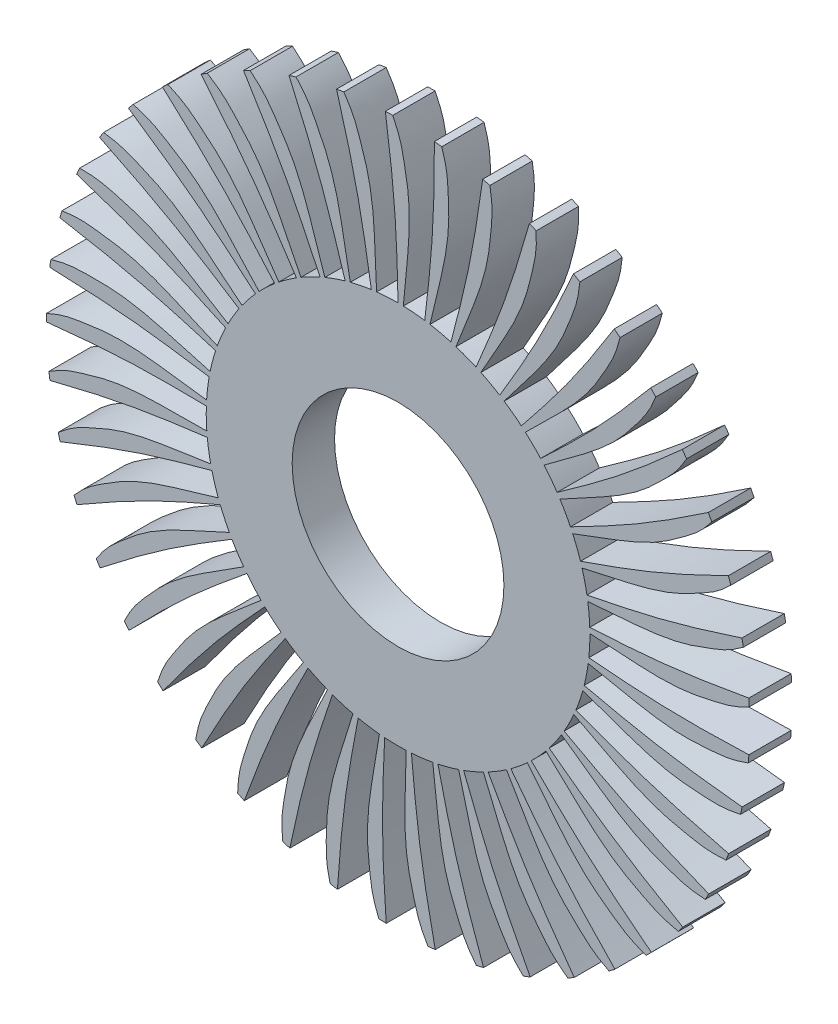
SolidWorks part; units mm, degrees
ref_plane "Front Plane" through (0, 0, 0) normal (0, 0, 1) x (1, 0, 0)
ref_plane "Top Plane" through (0, 0, 0) normal (0, 1, 0) x (1, 0, 0)
ref_plane "Right Plane" through (0, 0, 0) normal (1, 0, 0) x (0, 0, -1)
sketch "Sketch1" plane through (0, 0, 0) normal (0, 0, 1) x (1, 0, 0)
  arc A0 (49.9392, 174.1585) -> (30.1567, 178.6496) centre (0, 0) ccw
  arc A1 (-5, 332.0837) -> (-12, 331.9045) centre (0, 0) ccw
  arc A2 (41.2658, 329.5478) -> (34.309, 330.3445) centre (0, 0) ccw
  arc A3 (86.7284, 320.5976) -> (79.9501, 322.3548) centre (0, 0) ccw
  arc A4 (130.5029, 305.4073) -> (124.0352, 308.0907) centre (0, 0) ccw
  arc A5 (171.7373, 284.2726) -> (165.706, 287.83) centre (0, 0) ccw
  arc A6 (209.6291, 257.6048) -> (204.1516, 261.9671) centre (0, 0) ccw
  arc A7 (243.4407, 225.9231) -> (238.6236, 231.0052) centre (0, 0) ccw
  arc A8 (272.5139, 189.8441) -> (268.451, 195.5471) centre (0, 0) ccw
  arc A9 (296.283, 150.0699) -> (293.0534, 156.2829) centre (0, 0) ccw
  arc A10 (314.2853, 107.3748) -> (311.9518, 113.9768) centre (0, 0) ccw
  arc A11 (326.1704, 62.5898) -> (324.7784, 69.4523) centre (0, 0) ccw
  arc A12 (331.707, 16.5865) -> (331.2835, 23.576) centre (0, 0) ccw
  arc A13 (330.7872, -29.7396) -> (331.3407, -22.7592) centre (0, 0) ccw
  arc A14 (323.4291, -75.4869) -> (324.9486, -68.6514) centre (0, 0) ccw
  arc A15 (309.7757, -119.7648) -> (312.2318, -113.2074) centre (0, 0) ccw
  arc A16 (290.093, -161.7117) -> (293.4378, -155.56) centre (0, 0) ccw
  arc A17 (264.7639, -200.5111) -> (268.9323, -194.8847) centre (0, 0) ccw
  arc A18 (234.2815, -235.4078) -> (239.1923, -230.4162) centre (0, 0) ccw
  arc A19 (199.239, -265.7225) -> (204.7968, -261.463) centre (0, 0) ccw
  arc A20 (160.3186, -290.8652) -> (166.4151, -287.4206) centre (0, 0) ccw
  arc A21 (118.2778, -310.3465) -> (124.7943, -307.784) centre (0, 0) ccw
  arc A22 (73.9348, -323.7874) -> (80.7446, -322.1567) centre (0, 0) ccw
  arc A23 (28.1528, -330.926) -> (35.1233, -330.2589) centre (0, 0) ccw
  arc A24 (-18.1772, -331.6236) -> (-11.1817, -331.9331) centre (0, 0) ccw
  arc A25 (-64.1534, -325.8665) -> (-57.2691, -327.1466) centre (0, 0) ccw
  arc A26 (-108.8809, -313.7667) -> (-102.2417, -315.9925) centre (0, 0) ccw
  arc A27 (-151.4891, -295.5599) -> (-145.2244, -298.688) centre (0, 0) ccw
  arc A28 (-191.1488, -271.6003) -> (-185.3804, -275.5698) centre (0, 0) ccw
  arc A29 (-227.0881, -242.3543) -> (-221.9282, -247.088) centre (0, 0) ccw
  arc A30 (-258.6073, -208.3912) -> (-254.1564, -213.797) centre (0, 0) ccw
  arc A31 (-285.093, -170.372) -> (-281.4378, -176.3446) centre (0, 0) ccw
  arc A32 (-306.0297, -129.0367) -> (-303.2412, -135.4598) centre (0, 0) ccw
  arc A33 (-321.0098, -85.1898) -> (-319.1425, -91.9385) centre (0, 0) ccw
  arc A34 (-329.7419, -39.6848) -> (-328.832, -46.6277) centre (0, 0) ccw
  arc A35 (-332.0559, 6.5926) -> (-332.1211, -0.4094) centre (0, 0) ccw
  arc A36 (-327.9069, 52.7417) -> (-328.9459, 45.8169) centre (0, 0) ccw
  arc A37 (-317.3755, 97.8642) -> (-319.3682, 91.1515) centre (0, 0) ccw
  arc A38 (-300.6668, 141.082) -> (-303.5743, 134.7118) centre (0, 0) ccw
  arc A39 (-278.1059, 181.5537) -> (-281.8716, 175.6502) centre (0, 0) ccw
  arc A40 (-250.132, 218.4917) -> (-254.6827, 213.1697) centre (0, 0) ccw
  arc A41 (-217.2895, 251.177) -> (-222.5367, 246.5402) centre (0, 0) ccw
  arc A42 (-180.2178, 278.9734) -> (-186.0592, 275.112) centre (0, 0) ccw
  arc A43 (-139.6384, 301.3399) -> (-145.9603, 298.329) centre (0, 0) ccw
  arc A44 (-96.341, 317.8412) -> (-103.0204, 315.7395) centre (0, 0) ccw
  arc A45 (-51.1685, 328.1561) -> (-58.0754, 327.0044) centre (0, 0) ccw
  arc A46 (25.215, 179.4138) -> (5, 181.108) centre (0, 0) ccw
  arc A47 (0, 181.177) -> (-20.254, 180.0413) centre (0, 0) ccw
  arc A48 (-25.215, 179.4138) -> (-45.1138, 175.4704) centre (0, 0) ccw
  arc A49 (-49.9392, 174.1585) -> (-69.0955, 167.4841) centre (0, 0) ccw
  arc A50 (-73.6913, 165.5134) -> (-91.7324, 156.2379) centre (0, 0) ccw
  arc A51 (-96.0092, 153.6468) -> (-112.5838, 141.9507) centre (0, 0) ccw
  arc A52 (-116.4583, 138.7896) -> (-131.2438, 124.9006) centre (0, 0) ccw
  arc A53 (73.6913, 165.5134) -> (54.7264, 172.714) centre (0, 0) ccw
  arc A54 (96.0092, 153.6468) -> (78.231, 163.4167) centre (0, 0) ccw
  arc A55 (116.4583, 138.7896) -> (100.2129, 150.9387) centre (0, 0) ccw
  arc A56 (134.6408, 121.2311) -> (120.2442, 135.5228) centre (0, 0) ccw
  arc A57 (150.2026, 101.3129) -> (137.9351, 117.4692) centre (0, 0) ccw
  arc A58 (172.3096, 55.9868) -> (164.9707, 74.8986) centre (0, 0) ccw
  arc A59 (178.4245, 31.4611) -> (173.789, 51.2102) centre (0, 0) ccw
  arc A60 (181.0667, 6.323) -> (179.2248, 26.525) centre (0, 0) ccw
  arc A61 (180.1845, -18.9382) -> (181.1722, 1.3236) centre (0, 0) ccw
  arc A62 (175.7953, -43.8307) -> (179.5932, -23.9036) centre (0, 0) ccw
  arc A63 (167.9844, -67.8701) -> (174.5187, -48.6655) centre (0, 0) ccw
  arc A64 (142.7694, -111.5437) -> (154.3441, -94.8841) centre (0, 0) ccw
  arc A65 (125.8561, -130.3278) -> (139.6368, -115.4413) centre (0, 0) ccw
  arc A66 (106.4932, -146.5753) -> (122.2115, -133.7515) centre (0, 0) ccw
  arc A67 (85.0575, -159.9698) -> (102.4075, -149.4584) centre (0, 0) ccw
  arc A68 (61.9662, -170.2507) -> (80.6103, -162.2562) centre (0, 0) ccw
  arc A69 (37.6688, -177.2179) -> (57.2441, -171.896) centre (0, 0) ccw
  arc A70 (12.6383, -180.7357) -> (32.7637, -178.1899) centre (0, 0) ccw
  arc A71 (-12.6383, -180.7357) -> (7.6456, -181.0156) centre (0, 0) ccw
  arc A72 (-37.6688, -177.2179) -> (-17.6213, -180.3181) centre (0, 0) ccw
  arc A73 (-61.9662, -170.2507) -> (-42.5452, -176.1108) centre (0, 0) ccw
  arc A74 (-106.4932, -146.5753) -> (-89.4398, -157.5615) centre (0, 0) ccw
  arc A75 (-85.0575, -159.9698) -> (-66.6411, -168.4758) centre (0, 0) ccw
  arc A76 (-125.8561, -130.3278) -> (-110.4977, -143.5805) centre (0, 0) ccw
  arc A77 (-142.7694, -111.5437) -> (-129.4049, -126.8049) centre (0, 0) ccw
  arc A78 (-156.9039, -90.5885) -> (-145.7934, -107.5612) centre (0, 0) ccw
  arc A79 (-167.9844, -67.8701) -> (-159.3441, -86.2239) centre (0, 0) ccw
  arc A80 (-175.7953, -43.8307) -> (-169.7935, -63.2083) centre (0, 0) ccw
  arc A81 (-180.1845, -18.9382) -> (-176.9379, -38.9625) centre (0, 0) ccw
  arc A82 (-181.0667, 6.323) -> (-180.6385, -13.9583) centre (0, 0) ccw
  arc A83 (-178.4245, 31.4611) -> (-180.8232, 11.3175) centre (0, 0) ccw
  arc A84 (-172.3096, 55.9868) -> (-177.4883, 36.3731) centre (0, 0) ccw
  arc A85 (-162.8408, 79.4228) -> (-170.6989, 60.7207) centre (0, 0) ccw
  arc A86 (-150.2026, 101.3129) -> (-160.5869, 83.8865) centre (0, 0) ccw
  arc A87 (-134.6408, 121.2311) -> (-147.3494, 105.4195) centre (0, 0) ccw
  arc A88 (162.8408, 79.4228) -> (152.9413, 97.1291) centre (0, 0) ccw
  arc A89 (156.9039, -90.5885) -> (166.0474, -72.4802) centre (0, 0) ccw
  spline S0 degree 3 poles (5, 181.108) (8.4553, 222.2941) (14.1234, 253.7396) (4.4151, 306.3774) (2.5992, 316.7945) (-5, 332.0837) knots 0 0 0 0 0.601818 0.701818 1 1 1 1
  spline S1 degree 3 poles (0, 181.177) (-1.2031, 233.7472) (-2.136, 263.2326) (-12, 331.9045) knots 0 0 0 0 1 1 1 1
  spline S2 degree 3 poles (30.1567, 178.6496) (39.3104, 218.954) (49.2996, 249.3046) (47.0117, 302.7813) (46.6632, 313.3498) (41.2658, 329.5478) knots 0 0 0 0 0.601818 0.701818 1 1 1 1
  spline S3 degree 3 poles (25.215, 179.4138) (31.3399, 231.6398) (34.5197, 260.9681) (34.309, 330.3445) knots 0 0 0 0 1 1 1 1
  spline S4 degree 3 poles (54.7264, 172.714) (69.4003, 211.3522) (83.5164, 240.0172) (88.6932, 293.2919) (89.8189, 303.806) (86.7284, 320.5976) knots 0 0 0 0 0.601818 0.701818 1 1 1 1
  spline S5 degree 3 poles (49.9392, 174.1585) (63.273, 225.0238) (70.5035, 253.6242) (79.9501, 322.3548) knots 0 0 0 0 1 1 1 1
  spline S6 degree 3 poles (78.231, 163.4167) (98.1394, 199.6366) (116.1075, 226.0581) (128.6483, 278.0939) (131.2264, 288.349) (130.5029, 305.4073) knots 0 0 0 0 0.601818 0.701818 1 1 1 1
  spline S7 degree 3 poles (73.6913, 165.5134) (93.9744, 214.028) (105.115, 241.3438) (124.0352, 308.0907) knots 0 0 0 0 1 1 1 1
  spline S8 degree 3 poles (100.2129, 150.9387) (124.9684, 184.0354) (146.4388, 207.6991) (166.0995, 257.4831) (170.0798, 267.2797) (171.7373, 284.2726) knots 0 0 0 0 0.601818 0.701818 1 1 1 1
  spline S9 degree 3 poles (96.0092, 153.6468) (122.8468, 198.8664) (137.6806, 224.3658) (165.706, 287.83) knots 0 0 0 0 1 1 1 1
  spline S10 degree 3 poles (120.2442, 135.5228) (149.365, 164.8522) (173.9198, 185.2975) (200.3178, 231.8607) (205.6227, 241.008) (209.6291, 257.6048) knots 0 0 0 0 0.601818 0.701818 1 1 1 1
  spline S11 degree 3 poles (116.4583, 138.7896) (149.3281, 179.834) (167.5664, 203.0209) (204.1516, 261.9671) knots 0 0 0 0 1 1 1 1
  spline S12 degree 3 poles (137.9351, 117.4692) (170.8544, 142.4602) (198.0156, 159.2892) (230.6371, 201.7254) (237.1634, 210.0454) (243.4407, 225.9231) knots 0 0 0 0 0.601818 0.701818 1 1 1 1
  spline S13 degree 3 poles (134.6408, 121.2311) (172.903, 157.3015) (194.1907, 177.7244) (238.6236, 231.0052) knots 0 0 0 0 1 1 1 1
  spline S14 degree 3 poles (152.9413, 97.1291) (189.0183, 117.2955) (218.2573, 130.1806) (256.4673, 167.6638) (264.088, 174.9944) (272.5139, 189.8441) knots 0 0 0 0 0.601818 0.701818 1 1 1 1
  spline S15 degree 3 poles (150.2026, 101.3129) (193.1124, 131.7072) (217.0353, 148.9686) (268.451, 195.5471) knots 0 0 0 0 1 1 1 1
  spline S16 degree 3 poles (164.9707, 74.8986) (203.5031, 89.8477) (234.2509, 98.5381) (277.3057, 130.3387) (285.8725, 136.5374) (296.283, 150.0699) knots 0 0 0 0 0.601818 0.701818 1 1 1 1
  spline S17 degree 3 poles (162.8408, 79.4228) (209.5631, 103.5493) (235.6555, 117.3134) (293.0534, 156.2829) knots 0 0 0 0 1 1 1 1
  spline S18 degree 3 poles (173.789, 51.2102) (214.027, 60.6512) (245.685, 64.9777) (292.7466, 90.4768) (302.0927, 95.4229) (314.2853, 107.3748) knots 0 0 0 0 0.601818 0.701818 1 1 1 1
  spline S19 degree 3 poles (172.3096, 55.9868) (221.935, 73.3761) (249.689, 83.3748) (311.9518, 113.9768) knots 0 0 0 0 1 1 1 1
  spline S20 degree 3 poles (179.2248, 26.525) (220.3852, 30.2741) (252.3372, 30.1526) (302.4895, 48.8538) (312.4331, 52.4511) (326.1704, 62.5898) knots 0 0 0 0 0.601818 0.701818 1 1 1 1
  spline S21 degree 3 poles (178.4245, 31.4611) (229.9871, 41.7746) (258.8626, 47.8134) (324.7784, 69.4523) knots 0 0 0 0 1 1 1 1
  spline S22 degree 3 poles (181.1722, 1.3236) (222.4537, -0.6922) (254.0779, -5.2594) (306.3449, 6.28) (316.6923, 8.4584) (331.707, 16.5865) knots 0 0 0 0 0.601818 0.701818 1 1 1 1
  spline S23 degree 3 poles (181.0667, 6.323) (233.5628, 9.36) (262.9977, 11.3214) (331.2835, 23.576) knots 0 0 0 0 1 1 1 1
  spline S24 degree 3 poles (179.5932, -23.9036) (220.1925, -31.645) (250.8733, -40.569) (304.2375, -36.4161) (314.7874, -35.699) (330.7872, -29.7396) knots 0 0 0 0 0.601818 0.701818 1 1 1 1
  spline S25 degree 3 poles (180.1845, -18.9382) (232.5924, -23.2367) (262.0139, -25.391) (331.3407, -22.7592) knots 0 0 0 0 1 1 1 1
  spline S26 degree 3 poles (174.5187, -48.6655) (213.6454, -61.9819) (242.7857, -75.089) (296.2086, -78.4034) (306.7556, -79.1615) (323.4291, -75.4869) knots 0 0 0 0 0.601818 0.701818 1 1 1 1
  spline S27 degree 3 poles (175.7953, -43.8307) (227.0949, -55.3812) (255.9302, -61.6092) (324.9486, -68.6514) knots 0 0 0 0 1 1 1 1
  spline S28 degree 3 poles (166.0474, -72.4802) (202.94, -91.1124) (229.9725, -108.1475) (282.4143, -118.8646) (292.7531, -121.0833) (309.7757, -119.7648) knots 0 0 0 0 0.601818 0.701818 1 1 1 1
  spline S29 degree 3 poles (167.9844, -67.8701) (217.1773, -86.4477) (244.8652, -96.6282) (312.2318, -113.2074) knots 0 0 0 0 1 1 1 1
  spline S30 degree 3 poles (154.3441, -94.8841) (188.2846, -118.4695) (212.6832, -139.101) (263.1231, -157.0123) (273.0525, -160.6482) (290.093, -161.7117) knots 0 0 0 0 0.601818 0.701818 1 1 1 1
  spline S31 degree 3 poles (156.9039, -90.5885) (203.0325, -115.8317) (229.0341, -129.7665) (293.4378, -155.56) knots 0 0 0 0 1 1 1 1
  spline S32 degree 3 poles (139.6368, -115.4413) (169.9645, -143.5208) (191.2543, -167.347) (238.7105, -192.1039) (248.0373, -197.0864) (264.7639, -200.5111) knots 0 0 0 0 0.601818 0.701818 1 1 1 1
  spline S33 degree 3 poles (142.7694, -111.5437) (184.936, -142.9611) (208.7452, -160.379) (268.9323, -194.8847) knots 0 0 0 0 1 1 1 1
  spline S34 degree 3 poles (122.2115, -133.7515) (148.3362, -165.7785) (166.1028, -192.3359) (209.6517, -223.4565) (218.1943, -229.6885) (234.2815, -235.4078) knots 0 0 0 0 0.601818 0.701818 1 1 1 1
  spline S35 degree 3 poles (125.8561, -130.3278) (163.2399, -167.3079) (184.3933, -187.8699) (239.1923, -230.4162) knots 0 0 0 0 1 1 1 1
  spline S36 degree 3 poles (102.4075, -149.4584) (123.8207, -184.8096) (137.7183, -213.5811) (176.5122, -250.4597) (184.1044, -257.8199) (199.239, -265.7225) knots 0 0 0 0 0.601818 0.701818 1 1 1 1
  spline S37 degree 3 poles (106.4932, -146.5753) (138.3665, -188.3983) (156.4523, -211.7041) (204.7968, -261.463) knots 0 0 0 0 1 1 1 1
  spline S38 degree 3 poles (80.6103, -162.2562) (96.8951, -200.2435) (106.6533, -230.6693) (139.9372, -272.588) (146.4311, -280.9332) (160.3186, -290.8652) knots 0 0 0 0 0.601818 0.701818 1 1 1 1
  spline S39 degree 3 poles (85.0575, -159.9698) (110.7999, -205.8217) (125.4662, -231.4178) (166.4151, -287.4206) knots 0 0 0 0 1 1 1 1
  spline S40 degree 3 poles (57.2441, -171.896) (68.0837, -211.78) (73.5124, -243.2677) (100.6384, -289.4107) (105.9077, -298.5785) (118.2778, -310.3465) knots 0 0 0 0 0.601818 0.701818 1 1 1 1
  spline S41 degree 3 poles (61.9662, -170.2507) (81.0768, -219.239) (92.0381, -246.6272) (124.7943, -307.784) knots 0 0 0 0 1 1 1 1
  spline S42 degree 3 poles (32.7637, -178.1899) (37.947, -219.1944) (38.9407, -251.1312) (59.3808, -300.6003) (63.3229, -310.4122) (73.9348, -323.7874) knots 0 0 0 0 0.601818 0.701818 1 1 1 1
  spline S43 degree 3 poles (37.6688, -177.2179) (49.7756, -228.3891) (56.8185, -257.0363) (80.7446, -322.1567) knots 0 0 0 0 1 1 1 1
  spline S44 degree 3 poles (7.6456, -181.0156) (7.0717, -222.3424) (3.611, -254.1067) (16.9674, -305.9391) (19.5056, -316.2042) (28.1528, -330.926) knots 0 0 0 0 0.601818 0.701818 1 1 1 1
  spline S45 degree 3 poles (12.6383, -180.7357) (17.5055, -233.0938) (20.493, -262.4424) (35.1233, -330.2589) knots 0 0 0 0 1 1 1 1
  spline S46 degree 3 poles (-17.6213, -180.3181) (-23.9412, -221.1627) (-31.7889, -252.1363) (-25.7762, -305.3231) (-24.6913, -315.8415) (-18.1772, -331.6236) knots 0 0 0 0 0.601818 0.701818 1 1 1 1
  spline S47 degree 3 poles (-12.6383, -180.7357) (-15.1052, -233.2617) (-16.2314, -262.7404) (-11.1817, -331.9331) knots 0 0 0 0 1 1 1 1
  spline S48 degree 3 poles (-42.5452, -176.1108) (-54.4881, -215.6784) (-66.5702, -245.2583) (-68.0181, -298.7644) (-68.4077, -309.3314) (-64.1534, -325.8665) knots 0 0 0 0 0.601818 0.701818 1 1 1 1
  spline S49 degree 3 poles (-37.6688, -177.2179) (-47.422, -228.8894) (-52.6398, -257.9245) (-57.2691, -327.1466) knots 0 0 0 0 1 1 1 1
  spline S50 degree 3 poles (-66.6411, -168.4758) (-83.9744, -205.9962) (-100.0557, -233.6067) (-108.9361, -286.3905) (-110.7926, -296.8005) (-108.8809, -313.7667) knots 0 0 0 0 0.601818 0.701818 1 1 1 1
  spline S51 degree 3 poles (-61.9662, -170.2507) (-78.8157, -220.062) (-88.0237, -248.0883) (-102.2417, -315.9925) knots 0 0 0 0 1 1 1 1
  spline S52 degree 3 poles (-89.4398, -157.5615) (-111.8263, -192.3045) (-131.5937, -217.4082) (-147.7338, -268.4424) (-151.021, -278.4927) (-151.4891, -295.5599) knots 0 0 0 0 0.601818 0.701818 1 1 1 1
  spline S53 degree 3 poles (-85.0575, -159.9698) (-108.6754, -206.9513) (-121.6942, -233.4234) (-145.2244, -298.688) knots 0 0 0 0 1 1 1 1
  spline S54 degree 3 poles (-110.4977, -143.5805) (-137.5017, -174.8698) (-160.5704, -196.9781) (-183.656, -245.2694) (-188.31, -254.7644) (-191.1488, -271.6003) knots 0 0 0 0 0.601818 0.701818 1 1 1 1
  spline S55 degree 3 poles (-106.4932, -146.5753) (-136.4198, -189.8126) (-152.9962, -214.2152) (-185.3804, -275.5698) knots 0 0 0 0 1 1 1 1
  spline S56 degree 3 poles (-129.4049, -126.8049) (-160.5007, -154.0314) (-186.4218, -172.714) (-216.0036, -217.3225) (-221.9337, -226.0774) (-227.0881, -242.3543) knots 0 0 0 0 0.601818 0.701818 1 1 1 1
  spline S57 degree 3 poles (-125.8561, -130.3278) (-161.509, -168.9794) (-181.3202, -190.8375) (-221.9282, -247.088) knots 0 0 0 0 1 1 1 1
  spline S58 degree 3 poles (-145.7934, -107.5612) (-180.3757, -130.195) (-208.6447, -145.0883) (-244.1469, -185.1456) (-251.2377, -192.99) (-258.6073, -208.3912) knots 0 0 0 0 0.601818 0.701818 1 1 1 1
  spline S59 degree 3 poles (-142.7694, -111.5437) (-183.4546, -144.8572) (-206.1151, -163.7454) (-254.1564, -213.797) knots 0 0 0 0 1 1 1 1
  spline S60 degree 3 poles (-159.3441, -86.2239) (-196.7399, -103.8245) (-226.8066, -114.6386) (-267.5382, -149.3651) (-275.6517, -156.1463) (-285.093, -170.372) knots 0 0 0 0 0.601818 0.701818 1 1 1 1
  spline S61 degree 3 poles (-156.9039, -90.5885) (-201.8294, -117.9155) (-226.8981, -133.4661) (-281.4378, -176.3446) knots 0 0 0 0 1 1 1 1
  spline S62 degree 3 poles (-169.7935, -63.2083) (-209.2749, -75.4332) (-240.5539, -81.9576) (-285.7221, -110.6774) (-294.7005, -116.2634) (-306.0297, -129.0367) knots 0 0 0 0 0.601818 0.701818 1 1 1 1
  spline S63 degree 3 poles (-167.9844, -67.8701) (-216.2759, -88.6787) (-243.2649, -100.5891) (-303.2412, -135.4598) knots 0 0 0 0 1 1 1 1
  spline S64 degree 3 poles (-176.9379, -38.9625) (-217.7365, -45.5737) (-249.6192, -47.6813) (-298.3448, -69.8354) (-308.0132, -74.1176) (-321.0098, -85.1898) knots 0 0 0 0 0.601818 0.701818 1 1 1 1
  spline S65 degree 3 poles (-175.7953, -43.8307) (-226.5128, -57.7159) (-254.8967, -65.7543) (-319.1425, -91.9385) knots 0 0 0 0 1 1 1 1
  spline S66 degree 3 poles (-180.6385, -13.9583) (-221.9601, -14.8271) (-253.8258, -12.477) (-305.1606, -27.6342) (-315.3308, -30.5291) (-329.7419, -39.6848) knots 0 0 0 0 0.601818 0.701818 1 1 1 1
  spline S67 degree 3 poles (-180.1845, -18.9382) (-232.3409, -25.6297) (-261.5673, -29.6396) (-328.832, -46.6277) knots 0 0 0 0 1 1 1 1
  spline S68 degree 3 poles (-180.8232, 11.3175) (-221.8636, 16.2081) (-253.0921, 22.9702) (-306.0367, 15.1049) (-316.5109, 13.6536) (-332.0559, 6.5926) knots 0 0 0 0 0.601818 0.701818 1 1 1 1
  spline S69 degree 3 poles (-181.0667, 6.323) (-233.6468, 6.9553) (-263.1468, 7.052) (-332.1211, -0.4094) knots 0 0 0 0 1 1 1 1
  spline S70 degree 3 poles (-177.4883, 36.3731) (-217.4487, 46.9278) (-247.4322, 57.9702) (-300.9562, 57.5499) (-311.5304, 57.5705) (-327.9069, 52.7417) knots 0 0 0 0 0.601818 0.701818 1 1 1 1
  spline S71 degree 3 poles (-178.4245, 31.4611) (-230.4049, 39.4049) (-259.6044, 43.6063) (-328.9459, 45.8169) knots 0 0 0 0 1 1 1 1
  spline S72 degree 3 poles (-170.6989, 60.7207) (-208.8014, 76.7341) (-236.9563, 91.842) (-290.0179, 98.8749) (-300.4863, 100.3669) (-317.3755, 97.8642) knots 0 0 0 0 0.601818 0.701818 1 1 1 1
  spline S73 degree 3 poles (-172.3096, 55.9868) (-222.6785, 71.0876) (-251.0092, 79.3119) (-319.3682, 91.1515) knots 0 0 0 0 1 1 1 1
  spline S74 degree 3 poles (-160.5869, 83.8865) (-196.09, 105.0469) (-221.8683, 123.9261) (-273.4347, 138.2753) (-283.5936, 141.2097) (-300.6668, 141.082) knots 0 0 0 0 0.601818 0.701818 1 1 1 1
  spline S75 degree 3 poles (-162.8408, 79.4228) (-210.618, 101.3867) (-237.5283, 113.4738) (-303.5743, 134.7118) knots 0 0 0 0 1 1 1 1
  spline S76 degree 3 poles (-147.3494, 105.4195) (-179.562, 131.315) (-202.4619, 153.5982) (-251.5295, 174.9844) (-261.1811, 179.3041) (-278.1059, 181.5537) knots 0 0 0 0 0.601818 0.701818 1 1 1 1
  spline S77 degree 3 poles (-150.2026, 101.3129) (-194.4579, 129.7123) (-219.4242, 145.427) (-281.8716, 175.6502) knots 0 0 0 0 1 1 1 1
  spline S78 degree 3 poles (-131.2438, 124.9006) (-159.539, 155.0273) (-179.1149, 180.2806) (-224.7285, 208.2876) (-233.685, 213.9085) (-250.132, 218.4917) knots 0 0 0 0 0.601818 0.701818 1 1 1 1
  spline S79 degree 3 poles (-134.6408, 121.2311) (-174.513, 155.5133) (-197.0492, 174.5496) (-254.6827, 213.1697) knots 0 0 0 0 1 1 1 1
  spline S80 degree 3 poles (-112.5838, 141.9507) (-136.4107, 175.7221) (-152.2815, 203.4541) (-193.5534, 237.5367) (-201.6405, 244.3494) (-217.2895, 251.177) knots 0 0 0 0 0.601818 0.701818 1 1 1 1
  spline S81 degree 3 poles (-116.4583, 138.7896) (-151.1714, 178.2874) (-170.8389, 200.2749) (-222.5367, 246.5402) knots 0 0 0 0 1 1 1 1
  spline S82 degree 3 poles (-91.7324, 156.2379) (-110.6274, 192.9967) (-122.4842, 222.6676) (-158.6111, 262.1624) (-165.6713, 270.0344) (-180.2178, 278.9734) knots 0 0 0 0 0.601818 0.701818 1 1 1 1
  spline S83 degree 3 poles (-96.0092, 153.6468) (-124.8874, 197.5913) (-141.3035, 222.102) (-186.0592, 275.112) knots 0 0 0 0 1 1 1 1
  spline S84 degree 3 poles (-69.0955, 167.4841) (-82.6908, 206.5148) (-90.3028, 237.5471) (-120.5815, 281.6855) (-126.4775, 290.4634) (-139.6384, 301.3399) knots 0 0 0 0 0.601818 0.701818 1 1 1 1
  spline S85 degree 3 poles (-73.6913, 165.5134) (-96.1726, 213.0493) (-109.0177, 239.6062) (-145.9603, 298.329) knots 0 0 0 0 1 1 1 1
  spline S86 degree 3 poles (-45.1138, 175.4704) (-53.1448, 216.0134) (-56.3638, 247.8031) (-80.205, 295.7258) (-84.8219, 305.2389) (-96.341, 317.8412) knots 0 0 0 0 0.601818 0.701818 1 1 1 1
  spline S87 degree 3 poles (-49.9392, 174.1585) (-65.5859, 224.3606) (-74.61, 252.4467) (-103.0204, 315.7395) knots 0 0 0 0 1 1 1 1
  spline S88 degree 3 poles (-20.254, 180.0413) (-22.5643, 221.3075) (-21.3278, 253.2358) (-38.2673, 304.0102) (-41.5154, 314.0733) (-51.1685, 328.1561) knots 0 0 0 0 0.601818 0.701818 1 1 1 1
  spline S89 degree 3 poles (-25.215, 179.4138) (-33.7227, 231.3049) (-38.7501, 260.3736) (-58.0754, 327.0044) knots 0 0 0 0 1 1 1 1
  point P276 (0, 0)
  dimension "D1" = 151.3309
  dimension "D4" = 150.9804
  dimension "D2" = 5
  dimension "D3" = 7
  dimension "D5" = 45
extrude "Boss-Extrude1" add sketch "Sketch1" along normal blind 40
sketch "Sketch2" plane through (0, 0, 40) normal (0, 0, 1) x (1, 0, 0)
  circle A0 centre (0, 0) radius 100
extrude "Cut-Extrude1" cut sketch "Sketch2" against normal through all
